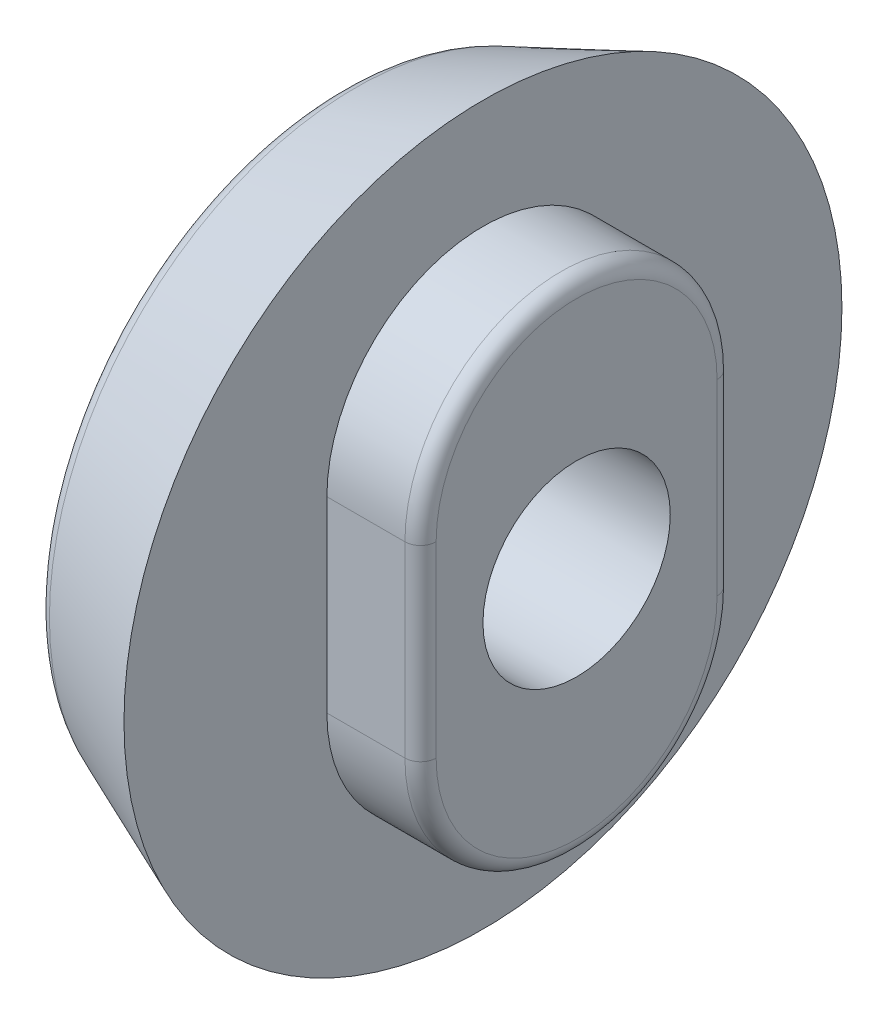
SolidWorks part; units mm, degrees
material "PBT Общее назначение"
ref_plane "Спереди" through (0, 0, 0) normal (0, 0, 1) x (1, 0, 0)
ref_plane "Сверху" through (0, 0, 0) normal (0, 1, 0) x (1, 0, 0)
ref_plane "Справа" through (0, 0, 0) normal (1, 0, 0) x (0, 0, -1)
sketch "Эскиз1" plane through (0, 0, 0) normal (0, 0, 1) x (1, 0, 0)
  line L0 (0, 3) -> (0, 7.55)
  line L1 (0, 7.55) -> (-1.7, 7.55)
  line L2 (-1.7, 7.55) -> (-1.7, 9.55)
  line L3 (-1.7, 9.55) -> (3, 11.5)
  line L4 (3, 11.5) -> (3, 7.0369)
  line L7 (3, 3) -> (0, 3)
  line L8 (0, 0) -> (8.7511, 0) construction
  line L9 (3, 7.0369) -> (3, 3)
  line L11 (-1.7, 7.55) -> (0, 7.55)
  line L12 (-1.7, 7.55) -> (-1.7, 3)
  line L13 (-1.7, 3) -> (0, 3)
  line L14 (0, 7.55) -> (0, 3)
  dimension "D1" = 4.55
  dimension "D2" = 3
  dimension "D3" = 2
  dimension "D4" = 1.7
  dimension "D5" = 4.4631
  dimension "D6" = 3
  dimension "D8" = 8.5
revolve "Повернуть1" add sketch "Эскиз1" angle 360 about L8
fillet "Скругление1" radius 1 1 edges at (-1.7, 0, 9.55)
sketch "Эскиз3" plane through (3, 0, 0) normal (1, 0, 0) x (0, 0, -1)
  line L0 (0, -3) -> (0, 3) construction
  line L1 (-5, -3) -> (-5, 3)
  line L2 (5, -3) -> (5, 3)
  circle A0 centre (0, 0) radius 3 construction
  arc A1 (-5, -3) -> (5, -3) centre (0, -3) ccw
  arc A2 (5, 3) -> (-5, 3) centre (0, 3) ccw
  circle A3 centre (0, 0) radius 3
  point P5 (0, 0)
  dimension "D1" = 5
extrude "Бобышка-Вытянуть1" add sketch "Эскиз3" along normal blind 3
fillet "Скругление3" radius 0.5 4 edges at (6, 8, 0) (6, 0, -5) (6, -8, 0) (6, 0, 5)
sketch "Эскиз4" plane through (-1.7, 0, 0) normal (-1, 0, 0) x (0, 0, 1)
  line L0 (0, 0) -> (0, 16.868) construction
  line L8 (4, 6.9282) -> (-4, 6.9282)
  line L9 (-4, 6.9282) -> (-8, 0)
  line L10 (-8, 0) -> (-4, -6.9282)
  line L11 (-4, -6.9282) -> (4, -6.9282)
  line L12 (4, -6.9282) -> (8, 0)
  line L13 (8, 0) -> (4, 6.9282)
  circle A0 centre (0, 0) radius 8 construction
  dimension "D1" = 16
extrude "Вырез-Вытянуть1" cut sketch "Эскиз4" against normal blind 2
